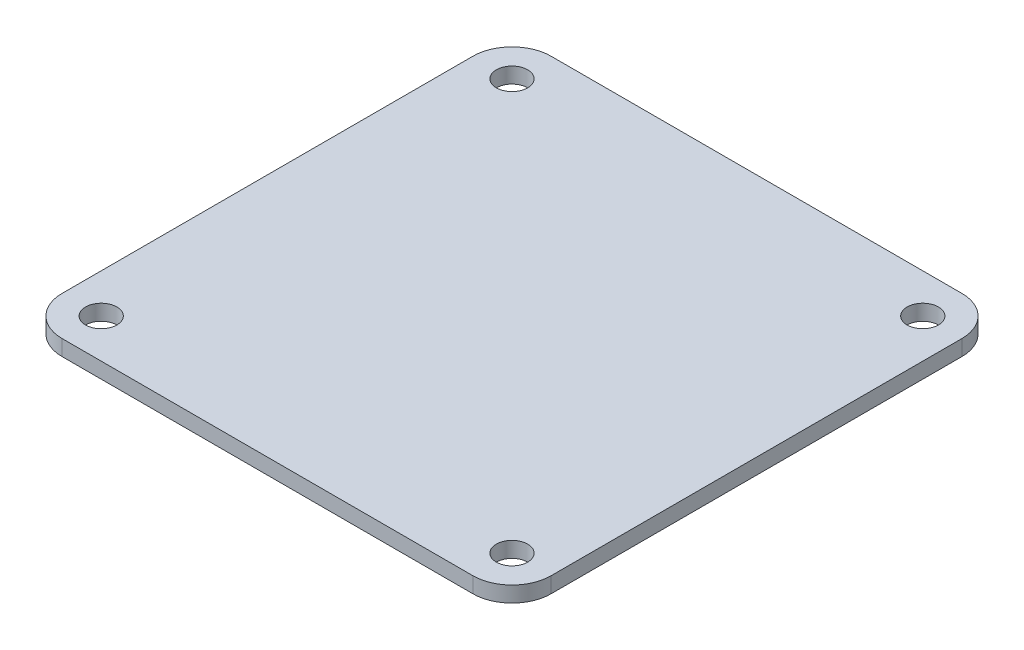
SolidWorks part; units mm, degrees
ref_plane "Plano frontal" through (0, 0, 0) normal (0, 0, 1) x (1, 0, 0)
ref_plane "Plano superior" through (0, 0, 0) normal (0, 1, 0) x (1, 0, 0)
ref_plane "Plano direito" through (0, 0, 0) normal (1, 0, 0) x (0, 0, -1)
sketch "Esboço1" plane through (0, 0, 0) normal (0, 1, 0) x (1, 0, 0)
  line L1 (-25, -25) -> (25, -25)
  line L2 (-25, -25) -> (-25, 25)
  line L3 (-25, 25) -> (25, 25)
  line L4 (25, -25) -> (25, 25)
  line L5 (-25, -25) -> (25, 25) construction
  line L6 (-25, 25) -> (25, -25) construction
  circle A0 centre (21, -21) radius 1.6
  circle A1 centre (21, 21) radius 1.6
  circle A2 centre (-21, 21) radius 1.6
  circle A3 centre (-21, -21) radius 1.6
  point P0 (0, 0)
  dimension "D1" = 50
  dimension "D2" = 50
  dimension "D3" = 4
  dimension "D4" = 4
  dimension "D5" = 4
  dimension "D6" = 4
extrude "Ressalto-extrusão1" add sketch "Esboço1" along normal blind 1.6
fillet "Filete1" radius 4 4 edges at (-25, 0.8, 25) (-25, 0.8, -25) (25, 0.8, -25) (25, 0.8, 25)
